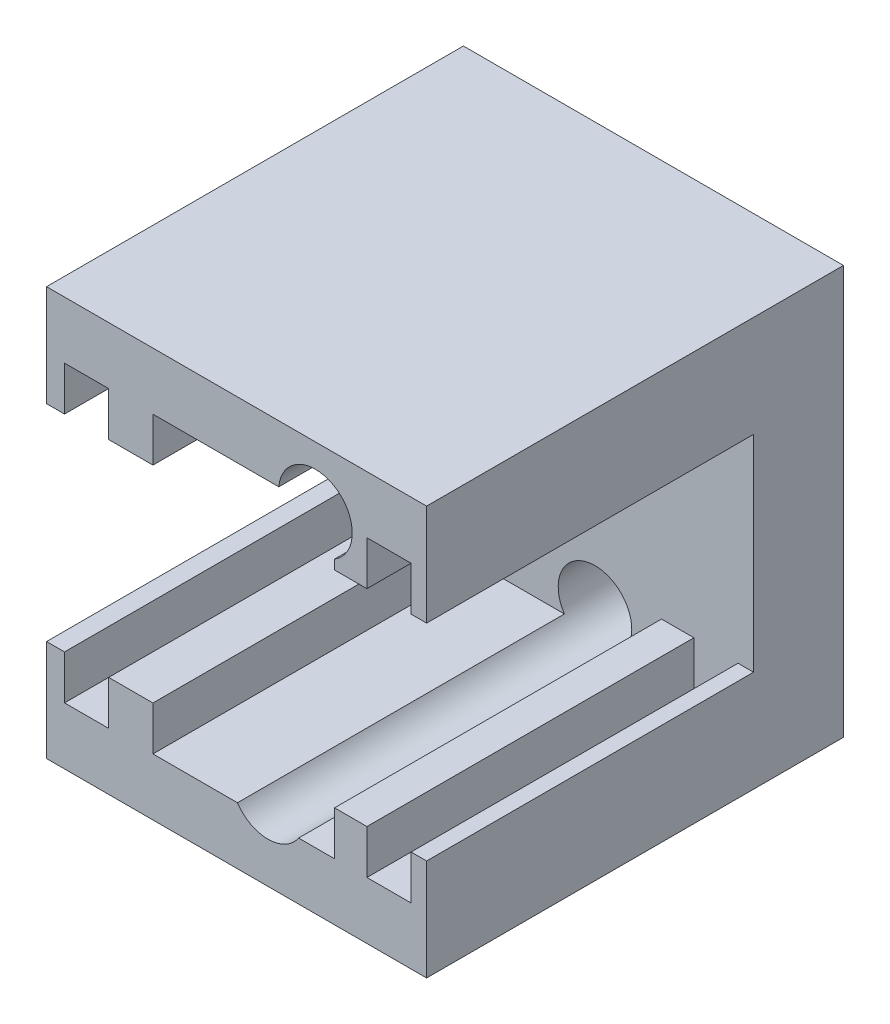
SolidWorks part; units mm, degrees
ref_plane "Front Plane" through (0, 0, 0) normal (1, 0, 0) x (0, 1, 0)
ref_plane "Top Plane" through (0, 0, 0) normal (0, 0, 1) x (0, 1, 0)
ref_plane "Right Plane" through (0, 0, 0) normal (0, 1, 0) x (-1, 0, 0)
sketch "Sketch1" plane through (0, 0, 0) normal (0, 0, 1) x (0, 1, 0)
  line L1 (-25, -23.25) -> (25, -23.25)
  line L2 (-25, -23.25) -> (-25, 23.25)
  line L3 (-25, 23.25) -> (25, 23.25)
  line L4 (25, -23.25) -> (25, 23.25)
  line L5 (-25, -23.25) -> (25, 23.25) construction
  line L6 (-25, 23.25) -> (25, -23.25) construction
  point P0 (0, 0)
  dimension "D1" = 46.5
  dimension "D2" = 50
extrude "Boss-Extrude1" add sketch "Sketch1" along normal blind 11
sketch "Sketch2" plane through (0, 0, 11) normal (0, 0, 1) x (1, 0, 0)
  line L0 (23.25, -25) -> (23.25, 25) construction
  line L1 (-23.25, 25) -> (23.25, 25)
  line L2 (-23.25, 25) -> (-23.25, 12.6)
  line L3 (-23.25, 12.6) -> (23.25, 12.6)
  line L4 (23.25, 25) -> (23.25, 12.6)
  line L5 (-23.25, -25) -> (23.25, -25) construction
  line L6 (-23.25, -25) -> (23.25, -25)
  line L7 (-23.25, -25) -> (-23.25, -12.6)
  line L8 (-23.25, -12.6) -> (23.25, -12.6)
  line L9 (23.25, -25) -> (23.25, -12.6)
  line L10 (-23.25, 25) -> (-23.25, -25) construction
  dimension "D1" = 12.4
  dimension "D2" = 12.4
extrude "Boss-Extrude2" add sketch "Sketch2" along normal blind 40
sketch "Sketch3" plane through (0, 0, 51) normal (0, 0, 1) x (1, 0, 0)
  line L0 (23.25, -12.6) -> (-23.25, -12.6) construction
  line L1 (-21.05, -12.6) -> (-15.65, -12.6)
  line L2 (-21.05, -12.6) -> (-21.05, -18)
  line L3 (-21.05, -18) -> (-15.65, -18)
  line L4 (-15.65, -12.6) -> (-15.65, -18)
  line L5 (-23.25, -12.6) -> (-23.25, -25) construction
  line L6 (15.95, -12.6) -> (21.35, -12.6)
  line L7 (15.95, -12.6) -> (15.95, -18)
  line L8 (15.95, -18) -> (21.35, -18)
  line L9 (21.35, -12.6) -> (21.35, -18)
  line L10 (-23.25, 0) -> (23.25, 0) construction
  line L11 (-23.25, 12.6) -> (-23.25, -12.6) construction
  line L12 (23.25, -12.6) -> (23.25, 12.6) construction
  line L13 (21.35, 12.6) -> (21.35, 18)
  line L14 (15.95, 18) -> (21.35, 18)
  line L15 (15.95, 12.6) -> (15.95, 18)
  line L16 (15.95, 12.6) -> (21.35, 12.6)
  line L17 (-15.65, 12.6) -> (-15.65, 18)
  line L18 (-21.05, 18) -> (-15.65, 18)
  line L19 (-21.05, 12.6) -> (-21.05, 18)
  line L20 (-21.05, 12.6) -> (-15.65, 12.6)
  line L21 (11.9877, 12.6) -> (11.9877, 18)
  line L22 (-10.2334, -12.6) -> (11.9877, -12.6)
  line L23 (-10.2334, -12.6) -> (-10.2334, -18)
  line L24 (-10.2334, -18) -> (11.9877, -18)
  line L25 (11.9877, -12.6) -> (11.9877, -18)
  line L26 (-10.2334, 12.6) -> (-10.2334, 18)
  line L27 (-10.2334, 18) -> (11.9877, 18)
  line L28 (-10.2334, 12.6) -> (11.9877, 12.6)
  dimension "D1" = 5.4
  dimension "D2" = 2.2
  dimension "D3" = 5.4
  dimension "D4" = 31.6
extrude "Cut-Extrude1" cut sketch "Sketch3" against normal blind 40
sketch "Sketch4" plane through (0, 0, 51) normal (0, 0, 1) x (1, 0, 0)
  line L0 (23.25, 12.6) -> (23.25, 25) construction
  line L1 (23.25, 25) -> (-23.25, 25) construction
  line L2 (-23.25, -25) -> (23.25, -25) construction
  line L4 (23.25, -25) -> (23.25, -12.6) construction
  circle A0 centre (9.65, 17.6) radius 4.5
  circle A1 centre (3.85, -15.5) radius 4.5
  point P10 (0, 0)
  point P12 (17.8798, -8.4487)
  dimension "D1" = 13.6
  dimension "D3" = 9.5
  dimension "D5" = 9
  dimension "D6" = 9
  dimension "D2" = 7.4
  dimension "D4" = 19.4
extrude "Cut-Extrude2" cut sketch "Sketch4" against normal blind 47.5 contours A0 | A1
sketch "Sketch5" plane through (0, 0, 3.5) normal (0, 0, 1) x (1, 0, 0)
  circle A0 centre (3.85, -15.5) radius 2.1
  circle A1 centre (9.65, 17.6) radius 2.1
extrude "Cut-Extrude3" cut sketch "Sketch5" against normal through all
